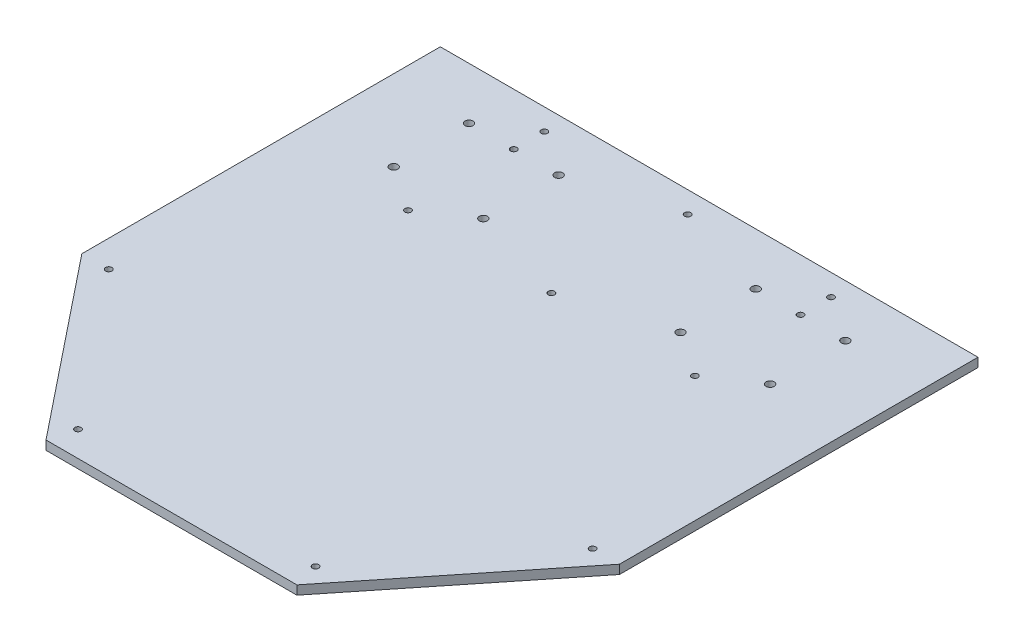
SolidWorks part; units mm, degrees
ref_plane "前基準面" through (0, 0, 0) normal (0, 0, 1) x (1, 0, 0)
ref_plane "上基準面" through (0, 0, 0) normal (0, 1, 0) x (1, 0, 0)
ref_plane "右基準面" through (0, 0, 0) normal (1, 0, 0) x (0, 0, -1)
sketch "草圖2" plane through (0, 0, 0) normal (0, 1, 0) x (1, 0, 0)
  line L0 (0, 150) -> (0, 0) construction
  line L1 (-150, 150) -> (150, 150)
  line L2 (-150, 150) -> (-150, -50)
  line L3 (-70, -150) -> (70, -150)
  line L4 (150, 150) -> (150, -50)
  line L5 (-150, 150) -> (150, -150) construction
  line L6 (-150, -150) -> (150, 150) construction
  line L7 (-105, 121) -> (-55, 121) construction
  line L8 (-105, 121) -> (-105, 79) construction
  line L9 (-105, 79) -> (-55, 79) construction
  line L10 (-55, 121) -> (-55, 79) construction
  line L11 (-105, 121) -> (-55, 79) construction
  line L12 (-105, 79) -> (-55, 121) construction
  line L13 (55, 121) -> (55, 79) construction
  line L14 (105, 79) -> (55, 79) construction
  line L15 (105, 121) -> (105, 79) construction
  line L16 (105, 121) -> (55, 121) construction
  line L17 (-150, -50) -> (-70, -150)
  line L18 (150, -50) -> (70, -150)
  line L19 (-150, -50) -> (-150, -150) construction
  line L20 (-150, -150) -> (-70, -150) construction
  line L21 (150, -50) -> (150, -150) construction
  line L22 (150, -150) -> (70, -150) construction
  circle A0 centre (-105, 121) radius 2.25
  circle A1 centre (-105, 79) radius 2.25
  circle A2 centre (-55, 79) radius 2.25
  circle A3 centre (-55, 121) radius 2.25
  circle A4 centre (55, 121) radius 2.25
  circle A5 centre (55, 79) radius 2.25
  circle A6 centre (105, 121) radius 2.25
  circle A7 centre (105, 79) radius 2.25
  point P0 (0, 0)
  point P6 (-80, 100)
  dimension "D7" = 4.5
  dimension "D1" = 42
  dimension "D2" = 50
  dimension "D3" = 50
  dimension "D4" = 70
  dimension "D5" = 300
  dimension "D6" = 300
  dimension "D8" = 100
  dimension "D9" = 80
extrude "填料-伸長2" add sketch "草圖2" along normal blind 5
sketch "草圖5" plane through (0, 5, 0) normal (0, 1, 0) x (1, 0, 0)
  line L0 (0, 0) -> (0, 91.4247) construction
  line L2 (-105, 121) -> (-105, 79) construction
  line L3 (-105, 79) -> (-105, 100) construction
  line L4 (-105, 100) -> (63.1861, 100) construction
  line L15 (-80, 75.6029) -> (-80, 51.5667) construction
  line L40 (0, 200) -> (0, 108.5753) construction
  circle A0 centre (0, 62) radius 1.75
  circle A1 centre (-80, 62) radius 1.75
  circle A2 centre (80, 62) radius 1.75
  circle A3 centre (80, 138) radius 1.75
  circle A4 centre (-80, 138) radius 1.75
  circle A5 centre (0, 138) radius 1.75
  dimension "D2" = 3.5
  dimension "D10" = 80
extrude "除料-伸長3" cut sketch "草圖5" against normal through all
sketch "草圖8" plane through (0, 5, 0) normal (0, 1, 0) x (1, 0, 0)
  line L0 (-105, 121) -> (-55, 121) construction
  line L1 (0, 138) -> (0, 62) construction
  line L2 (-150, -50) -> (-135, -50) construction
  line L3 (-135, -50) -> (-55, -150) construction
  line L4 (-70, -150) -> (70, -150) construction
  line L5 (-55, -150) -> (-70, -150) construction
  line L6 (-70, -150) -> (-150, -50) construction
  circle A0 centre (-55, 121) radius 2.25 construction
  circle A1 centre (-105, 121) radius 2.25 construction
  circle A2 centre (-55, 121) radius 2.25 construction
  circle A3 centre (-105, 121) radius 2.25 construction
  circle A4 centre (-80, 121) radius 1.75
  circle A5 centre (80, 121) radius 1.75
  circle A6 centre (-135, -50) radius 1.75
  circle A7 centre (-66.2835, -135.8956) radius 1.75
  circle A8 centre (135, -50) radius 1.75
  circle A9 centre (66.2835, -135.8956) radius 1.75
  dimension "D1" = 3.5
  dimension "D3" = 3.5
  dimension "D4" = 3.5
  dimension "D5" = 110
  dimension "D2" = 15
extrude "除料-伸長5" cut sketch "草圖8" against normal through all
